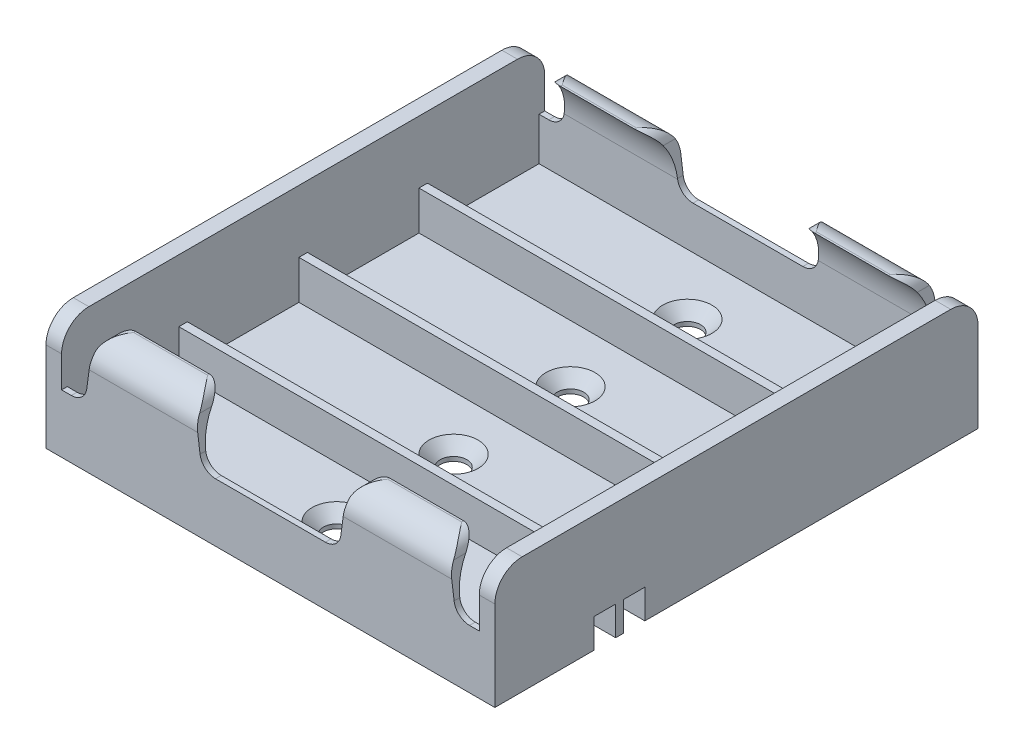
SolidWorks part; units mm, degrees
ref_plane "Front Plane" through (0, 0, 0) normal (0, 0, 1) x (1, 0, 0)
ref_plane "Top Plane" through (0, 0, 0) normal (0, 1, 0) x (1, 0, 0)
ref_plane "Right Plane" through (0, 0, 0) normal (1, 0, 0) x (0, 0, -1)
sketch "Sketch1" plane through (0, 0, 0) normal (1, 0, 0) x (0, 0, -1)
  line L0 (0, 0) -> (31, 0)
  line L1 (31, 0) -> (31, 11.5)
  line L2 (27.5, 15) -> (0, 15)
  line L3 (0, 15) -> (0, 0)
  line L4 (-31, 0) -> (0, 0) construction
  arc A0 (31, 11.5) -> (27.5, 15) centre (27.5, 11.5) ccw
  dimension "D3" = 3.5
  dimension "D1" = 15
  dimension "D2" = 62
extrude "Boss-Extrude1" add sketch "Sketch1" along normal mid plane 57.6
mirror "Mirror1" about plane through (28.8, 15, 0) normal (0, 0, -1) of "Boss-Extrude1"
sketch "Sketch2" plane through (28.8, 0, 0) normal (1, 0, 0) x (0, 0, -1)
  line L0 (-31, 0) -> (31, 0) construction
  line L1 (-18.25, 0) -> (-15.5, 0)
  line L2 (-18.25, 0) -> (-18.25, 3.75)
  line L3 (-18.25, 3.75) -> (-15.5, 3.75)
  line L4 (-15.5, 0) -> (-15.5, 3.75)
  line L5 (-31, 0) -> (-31, 11.5) construction
  line L6 (-14.5, 0) -> (-11.75, 0)
  line L7 (-14.5, 0) -> (-14.5, 3.75)
  line L8 (-14.5, 3.75) -> (-11.75, 3.75)
  line L9 (-11.75, 0) -> (-11.75, 3.75)
  dimension "D1" = 12.75
  dimension "D2" = 1
  dimension "D3" = 3.75
  dimension "D4" = 2.75
extrude "Cut-Extrude1" cut sketch "Sketch2" against normal blind 3.75
sketch "Sketch3" plane through (28.8, 0, 0) normal (1, 0, 0) x (0, 0, -1)
  line L0 (-30.27, 9.16) -> (-30.27, 2)
  line L1 (-30.27, 2) -> (-15.95, 2)
  line L2 (-15.95, 2) -> (-15.95, 9.16)
  line L3 (-31, 0) -> (-18.25, 0) construction
  line L4 (-31, 0) -> (-15.5, 0) construction
  line L5 (-15.5, 0) -> (0, 0) construction
  line L6 (-23.25, 0) -> (-23.11, 2) construction
  line L7 (-14.8633, 9.16) -> (-14.8633, 2)
  line L8 (-14.8633, 2) -> (-0.5433, 2)
  line L9 (-0.5433, 2) -> (-0.5433, 9.16)
  line L10 (-15.95, 2) -> (-15.4067, 2) construction
  line L11 (-15.4067, 2) -> (-14.8633, 2) construction
  line L12 (-0.5433, 2) -> (0, 2) construction
  line L13 (0, 2) -> (0, 0) construction
  arc A0 (-15.95, 9.16) -> (-30.27, 9.16) centre (-23.11, 9.16) ccw
  arc A1 (-30.27, 9.16) -> (-23.11, 2) centre (-23.11, 9.16) ccw construction
  arc A2 (-23.11, 2) -> (-15.95, 9.16) centre (-23.11, 9.16) ccw construction
  arc A3 (-14.8633, 9.16) -> (-0.5433, 9.16) centre (-7.7033, 9.16) cw
  dimension "D1" = 0.45
  dimension "D3" = 14.32
  dimension "D2" = 2
extrude "Cut-Extrude2" cut sketch "Sketch3" against normal offset from surface (53.6 mm away) 2 from offset 2 up to face at (-28.8, 9.075, 0) offset against normal yes
mirror "Mirror2" about plane through (0, 0, 0) normal (0, 0, 1) of "Cut-Extrude2"
sketch "Sketch4" plane through (0, 15, 0) normal (0, 1, 0) x (1, 0, 0)
  line L1 (-26.8, 27.2525) -> (26.8, 27.2525)
  line L2 (-26.8, 27.2525) -> (-26.8, -27.2525)
  line L3 (-26.8, -27.2525) -> (26.8, -27.2525)
  line L4 (26.8, 27.2525) -> (26.8, -27.2525)
extrude "Cut-Extrude3" cut sketch "Sketch4" against normal offset from surface (8 mm away) 5 up to face at (0, 2, -7.7033)
sketch "Sketch5" plane through (0, 2, 0) normal (0, 1, 0) x (1, 0, 0)
  line L0 (0, 22.5) -> (0, 7.5) construction
  line L1 (0, 7.5) -> (0, -7.5) construction
  line L2 (0, -7.5) -> (0, -22.5) construction
  point P2 (0, 0)
  point P5 (0, 22.5)
  point P8 (0, 7.5)
  point P9 (0, -7.5)
  point P10 (0, -22.5)
  dimension "D1" = 15
hole_wizard "CSK for M3 Flat Head Machine Screw1" positions "3DSketch1" profile "Sketch6" countersink size "M3" standard "ANSI Metric"
sketch3d "3DSketch1"
  point P0 (0, 2, -22.5)
  point P3 (0, 2, -7.5)
  point P6 (0, 2, 7.5)
  point P9 (0, 2, 22.5)
sketch "Sketch6" plane through (0, 2, -22.5) normal (1, 0, 0) x (0, 0, 1)
  line L0 (0, 0) -> (0, 8.8955)
  line L1 (0, 8.8955) -> (1.7, 7.874)
  line L2 (1.7, 7.874) -> (1.7, 1.45)
  line L3 (1.7, 1.45) -> (3.15, 0)
  line L5 (3.15, 0) -> (0, 0)
  line L6 (-1.7, 1.45) -> (-3.15, 0) construction
  line L10 (0, 8.8955) -> (-1.7, 7.874) construction
  line L11 (0, -6.35) -> (0, 107.95) construction
  dimension "Hole Dia." = 3.4
  dimension "Hole Depth" = 7.874
  dimension "Near C'Sink Dia." = 6.3
  dimension "Near C'Sink Angle" = 90
  dimension "Drill Angle" = 118
sketch "Sketch7" plane through (0, 0, 0) normal (0, 0, 1) x (1, 0, 0)
  line L0 (-26.8, 15) -> (-26.8, 7.5)
  line L1 (-9.5686, 13.2643) -> (-9.0314, 9.2357)
  line L2 (-26.8, 7.5) -> (-25.551, 7.5)
  line L3 (-23.8, 7.5) -> (-22.8, 15) construction
  line L4 (28.8, 15) -> (-28.8, 15) construction
  line L5 (-22.8, 15) -> (-26.8, 15)
  line L6 (-9.8, 15) -> (-8.8, 7.5) construction
  line L7 (-7.049, 7.5) -> (0, 7.5)
  line L9 (0, 15) -> (-9.8, 15)
  line L10 (28.8, 0) -> (-28.8, 0) construction
  line L13 (-23.0314, 13.2643) -> (-23.5686, 9.2357)
  line L16 (-22.8, 15) -> (-21.049, 15)
  line L18 (-11.551, 15) -> (-9.8, 15)
  line L19 (-25.551, 7.5) -> (-23.8, 7.5) construction
  line L20 (-8.8, 7.5) -> (-7.049, 7.5) construction
  line L21 (0, 15) -> (0, 7.5)
  arc A0 (-23.0314, 13.2643) -> (-21.049, 15) centre (-21.049, 13) cw
  arc A1 (-23.5686, 9.2357) -> (-25.551, 7.5) centre (-25.551, 9.5) cw
  arc A2 (-11.551, 15) -> (-9.5686, 13.2643) centre (-11.551, 13) cw
  arc A3 (-9.0314, 9.2357) -> (-7.049, 7.5) centre (-7.049, 9.5) ccw
  dimension "D5" = 2
  dimension "D1" = 7.5
  dimension "D2" = 3
  dimension "D3" = 4
  dimension "D4" = 15
extrude "Cut-Extrude4" cut sketch "Sketch7" against normal through all both and the other way through all
mirror "Mirror3" about plane through (0, 0, 0) normal (1, 0, 0) of "Cut-Extrude4"
